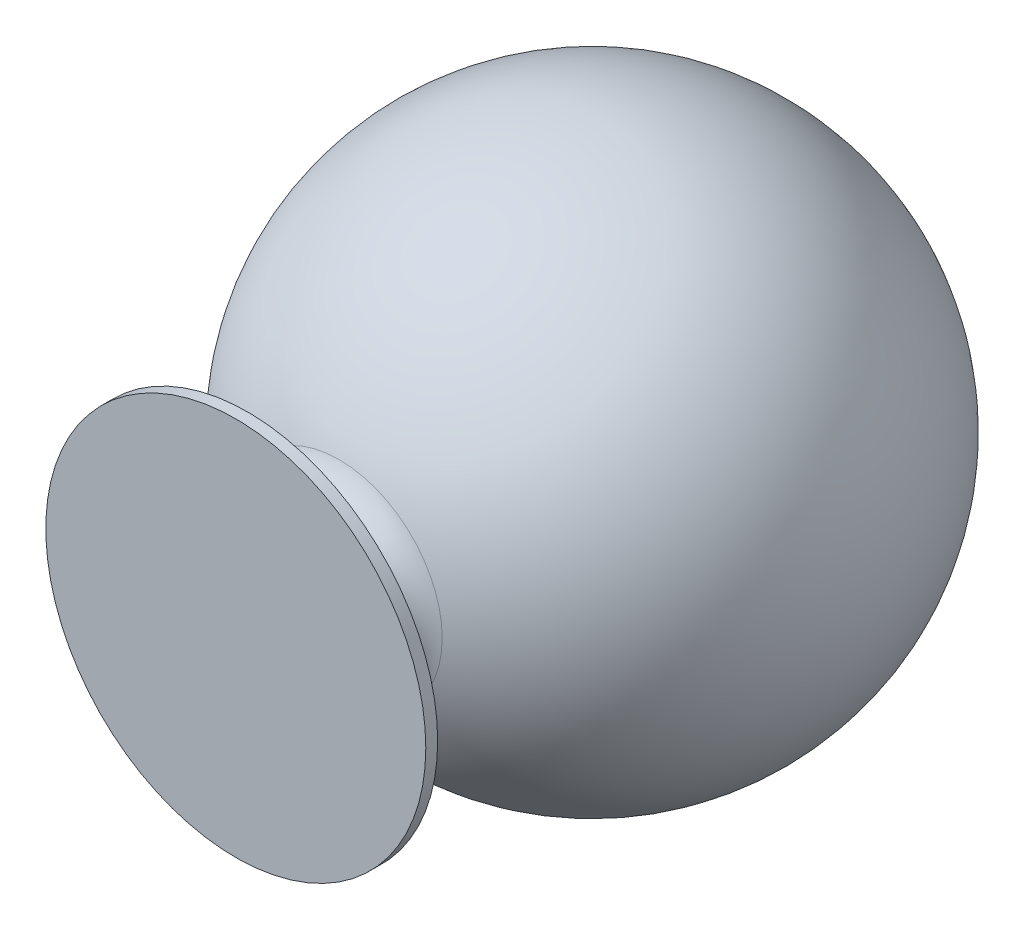
SolidWorks part; units mm, degrees
ref_plane "Front Plane" through (0, 0, 0) normal (0, 0, 1) x (1, 0, 0)
ref_plane "Top Plane" through (0, 0, 0) normal (0, 1, 0) x (1, 0, 0)
ref_plane "Right Plane" through (0, 0, 0) normal (1, 0, 0) x (0, 0, -1)
sketch "Sketch2" plane through (0, 0, 0) normal (0, 1, 0) x (1, 0, 0)
  line L0 (0, -29.9388) -> (0, 19.2321) construction
  line L1 (-16, -30) -> (-16, -29)
  line L2 (-16, -30) -> (0, -30)
  line L3 (0, 23) -> (0, -30)
  arc A0 (0, 23) -> (-8.6792, -21.2995) centre (0, 0) ccw
  arc A1 (-16, -29) -> (-8.9088, -27.8663) centre (-16, -6.2551) ccw
  arc A2 (-8.9088, -27.8663) -> (-8.6792, -21.2995) centre (-10, -24.5408) ccw
  dimension "D1" = 23
  dimension "D3" = 53
  dimension "D4" = 3.5
  dimension "D2" = 16
  dimension "D5" = 10
  dimension "D6" = 1
revolve "Revolve4" add sketch "Sketch2" angle 360 about L0
